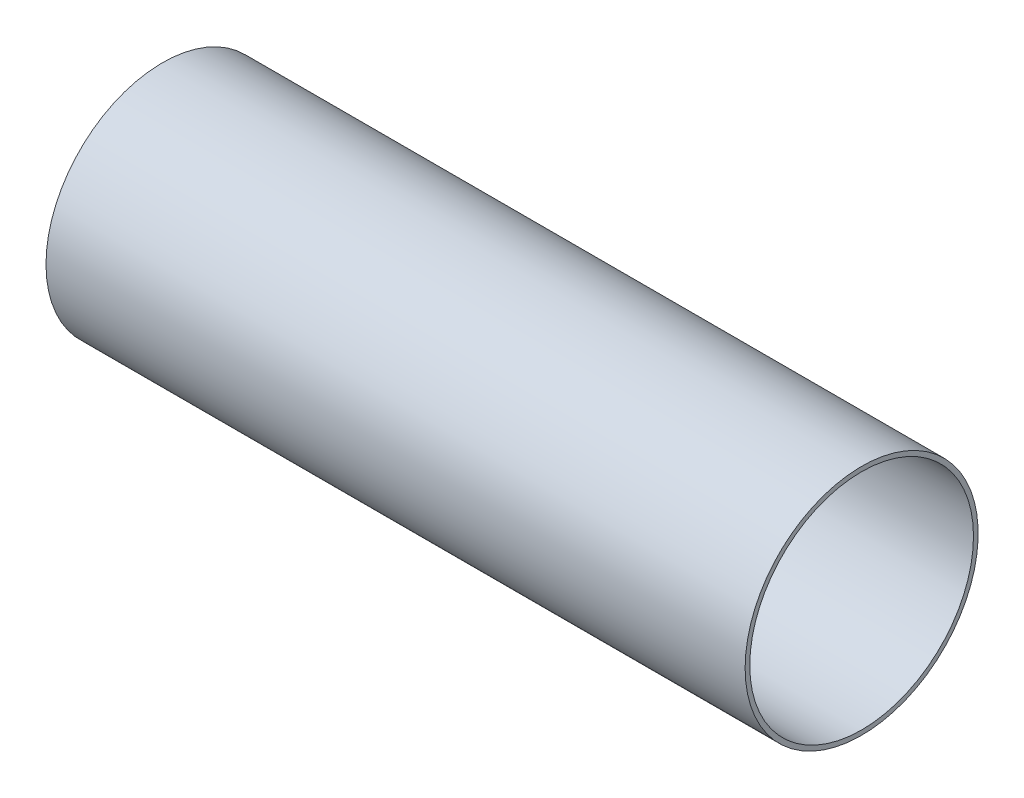
SolidWorks part; units mm, degrees
ref_plane "Спереди" through (0, 0, 0) normal (0, 0, 1) x (1, 0, 0)
ref_plane "Сверху" through (0, 0, 0) normal (0, 1, 0) x (1, 0, 0)
ref_plane "Справа" through (0, 0, 0) normal (1, 0, 0) x (0, 0, -1)
sketch "BeamSketch" plane through (0, 0, 0) normal (0, 0, 1) x (1, 0, 0)
  line L0 (-21.8905, 0) -> (29.9148, 0) construction
  line L1 (-150, 50) -> (150, 50)
  line L2 (-150, 50) -> (-150, 48)
  line L3 (-150, 48) -> (150, 48)
  line L4 (150, 50) -> (150, 48)
  point P4 (0, 48)
  dimension "depth" = 2
  dimension "externalDiameter" = 100
  dimension "length" = 300
revolve "Beam" add sketch "BeamSketch" angle 360 about L0
